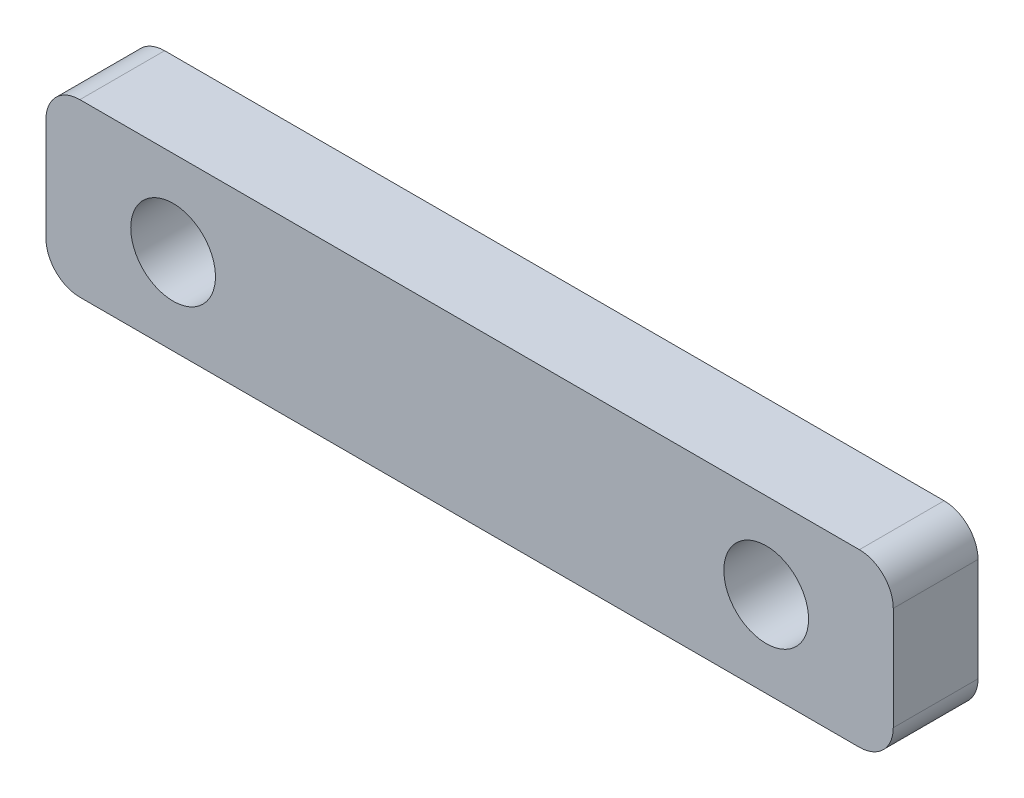
SolidWorks part; units mm, degrees
ref_plane "Plan de face" through (0, 0, 0) normal (0, 0, 1) x (1, 0, 0)
ref_plane "Plan de dessus" through (0, 0, 0) normal (0, 1, 0) x (1, 0, 0)
ref_plane "Plan de droite" through (0, 0, 0) normal (1, 0, 0) x (0, 0, -1)
sketch "Esquisse1" plane through (0, 0, 0) normal (0, 0, 1) x (1, 0, 0)
  line L0 (11.5443, 17.4111) -> (11.5443, -3.6239) construction
  line L1 (-11.4557, 13.9945) -> (34.5443, 13.9945)
  line L2 (-13.4557, 11.9945) -> (-13.4557, 5.8945)
  line L3 (-11.4557, 3.8945) -> (34.5443, 3.8945)
  line L4 (36.5443, 11.9945) -> (36.5443, 5.8945)
  line L5 (-13.4557, 13.9945) -> (36.5443, 3.8945) construction
  line L6 (-13.4557, 3.8945) -> (36.5443, 13.9945) construction
  circle A0 centre (29.0443, 8.9445) radius 2.5
  circle A1 centre (-5.9557, 8.9445) radius 2.5
  arc A2 (34.5443, 3.8945) -> (36.5443, 5.8945) centre (34.5443, 5.8945) ccw
  arc A3 (36.5443, 11.9945) -> (34.5443, 13.9945) centre (34.5443, 11.9945) ccw
  arc A4 (-11.4557, 3.8945) -> (-13.4557, 5.8945) centre (-11.4557, 5.8945) cw
  arc A5 (-13.4557, 11.9945) -> (-11.4557, 13.9945) centre (-11.4557, 11.9945) cw
  point P4 (11.5443, 8.9445)
  dimension "D5" = 5
  dimension "D6" = 2
  dimension "D1" = 50
  dimension "D2" = 10.1
  dimension "D3" = 7.5
  dimension "D4" = 5.05
extrude "Boss.-Extru.1" add sketch "Esquisse1" along normal blind 5
